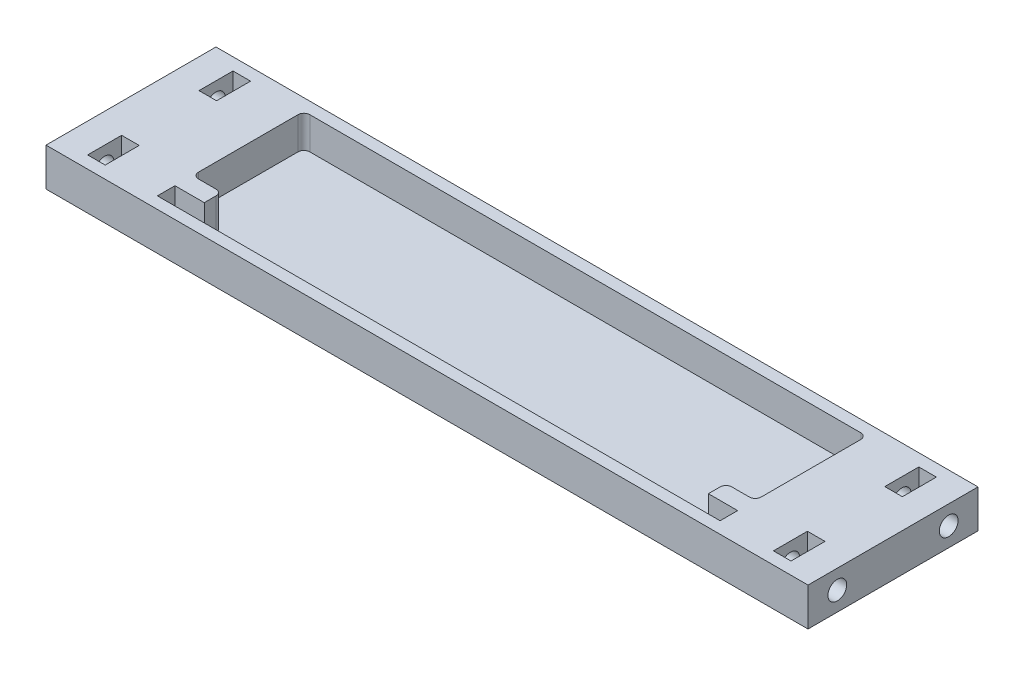
SolidWorks part; units mm, degrees
ref_plane "Alzado" through (0, 0, 0) normal (0, 0, 1) x (1, 0, 0)
ref_plane "Planta" through (0, 0, 0) normal (0, 1, 0) x (1, 0, 0)
ref_plane "Vista lateral" through (0, 0, 0) normal (1, 0, 0) x (0, 0, -1)
sketch "Croquis1" plane through (0, 0, 0) normal (0, 1, 0) x (1, 0, 0)
  line L1 (-65, -14.5) -> (65, -14.5)
  line L2 (-65, -14.5) -> (-65, 14.5)
  line L3 (-65, 14.5) -> (65, 14.5)
  line L4 (65, -14.5) -> (65, 14.5)
  line L5 (-65, -14.5) -> (65, 14.5) construction
  line L6 (-65, 14.5) -> (65, -14.5) construction
  point P0 (0, 0)
  dimension "D1" = 130
  dimension "D2" = 29
extrude "Saliente-Extruir1" add sketch "Croquis1" along normal blind 6.5
sketch "Croquis2" plane through (0, 6.5, 0) normal (0, 1, 0) x (1, 0, 0)
  line L0 (0, 14.5) -> (0, -14.5) construction
  line L1 (65, 14.5) -> (-65, 14.5) construction
  line L2 (-65, -14.5) -> (65, -14.5) construction
  line L3 (48, 12.5) -> (-48, 12.5)
  line L4 (-48, 12.5) -> (-48, -6.5)
  line L5 (-48, -6.5) -> (-43, -6.5)
  line L6 (-43, -6.5) -> (-43, -9.5)
  line L7 (-43, -9.5) -> (-48, -9.5)
  line L8 (-48, -9.5) -> (-48, -12.5)
  line L9 (-48, -12.5) -> (48, -12.5)
  line L10 (-65, 14.5) -> (-65, -14.5) construction
  line L11 (48, -9.5) -> (48, -12.5)
  line L12 (43, -9.5) -> (48, -9.5)
  line L13 (43, -6.5) -> (43, -9.5)
  line L14 (48, -6.5) -> (43, -6.5)
  line L15 (48, 12.5) -> (48, -6.5)
  point P18 (0, -12.5)
  point P23 (0, 12.5)
  dimension "D1" = 2
  dimension "D2" = 2
  dimension "D3" = 19
  dimension "D4" = 3
  dimension "D5" = 5
  dimension "D6" = 17
extrude "Cortar-Extruir1" cut sketch "Croquis2" against normal blind 5.5
sketch "Croquis3" plane through (0, 6.5, 0) normal (0, 1, 0) x (1, 0, 0)
  line L0 (-65, 14.5) -> (-65, -14.5) construction
  line L1 (-60, -6.6) -> (-57, -6.6)
  line L2 (-60, -6.6) -> (-60, -12.4)
  line L3 (-60, -12.4) -> (-57, -12.4)
  line L4 (-57, -6.6) -> (-57, -12.4)
  line L5 (-65, -14.5) -> (65, -14.5) construction
  line L6 (-3.575, 0) -> (3.575, 0) construction
  line L7 (-60, 12.4) -> (-57, 12.4)
  line L8 (-57, 6.6) -> (-57, 12.4)
  line L9 (-60, 6.6) -> (-57, 6.6)
  line L10 (-60, 6.6) -> (-60, 12.4)
  line L11 (0, -3.575) -> (0, 3.575) construction
  line L12 (60, -12.4) -> (57, -12.4)
  line L13 (57, -6.6) -> (57, -12.4)
  line L14 (60, -6.6) -> (57, -6.6)
  line L15 (60, -6.6) -> (60, -12.4)
  line L16 (60, 6.6) -> (60, 12.4)
  line L17 (60, 6.6) -> (57, 6.6)
  line L18 (57, 6.6) -> (57, 12.4)
  line L19 (60, 12.4) -> (57, 12.4)
  dimension "D1" = 3
  dimension "D2" = 5.8
  dimension "D3" = 5
  dimension "D4" = 2.1
extrude "Cortar-Extruir2" cut sketch "Croquis3" against normal through all
sketch "Croquis4" plane through (-65, 0, 0) normal (-1, 0, 0) x (0, 0, 1)
  line L0 (-14.5, 6.5) -> (14.5, 6.5) construction
  line L1 (-14.5, 6.5) -> (-14.5, 0) construction
  line L2 (0, -3.575) -> (0, 3.575) construction
  circle A0 centre (-9.5, 3.25) radius 1.6
  circle A1 centre (9.5, 3.25) radius 1.6
  dimension "D1" = 3.2
  dimension "D2" = 3.25
  dimension "D3" = 5
extrude "Cortar-Extruir3" cut sketch "Croquis4" against normal blind 15
sketch "Croquis5" plane through (65, 0, 0) normal (1, 0, 0) x (0, 0, -1)
  circle A0 centre (-9.5, 3.25) radius 1.6
  circle A1 centre (9.5, 3.25) radius 1.6
  dimension "D1" = 3.2
  dimension "D2" = 3.2
extrude "Cortar-Extruir4" cut sketch "Croquis5" against normal blind 15
fillet "Redondeo1" radius 1 6 edges at (43, 3.75, 6.5) (48, 3.75, 6.5) (48, 3.75, -12.5) (-48, 3.75, -12.5) (-48, 3.75, 6.5) (-43, 3.75, 6.5)
